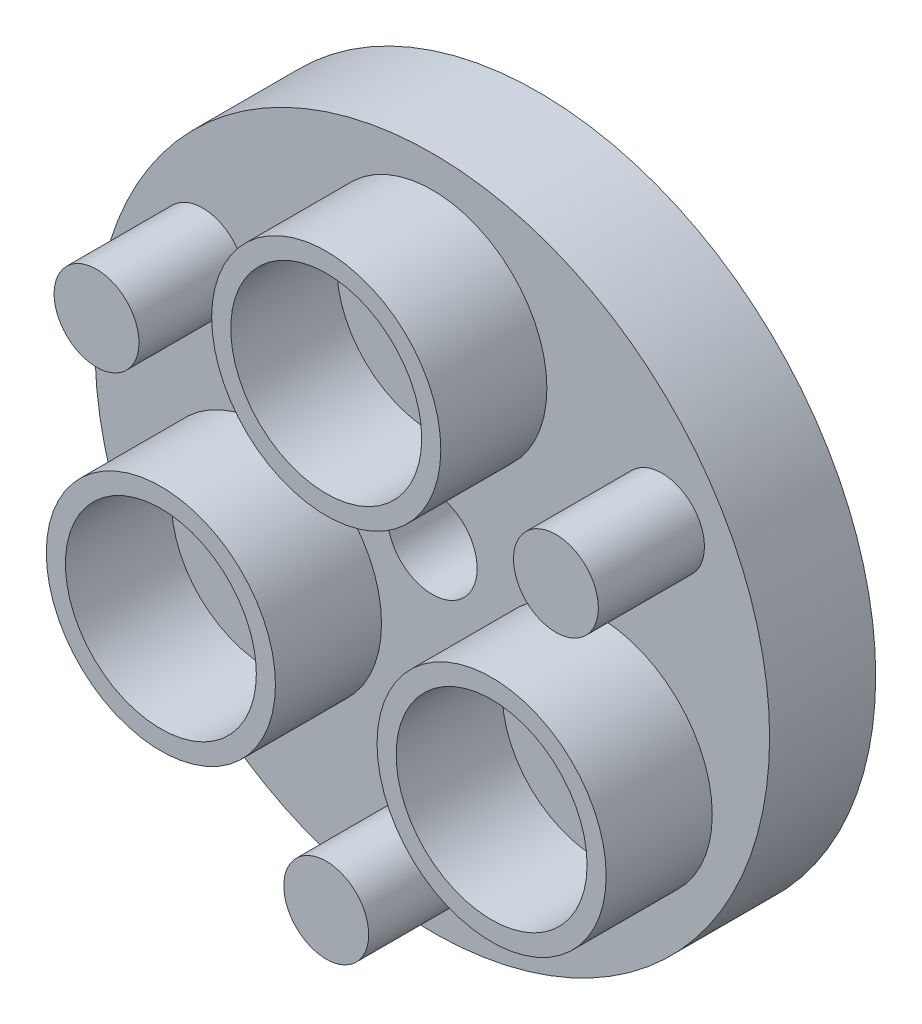
SolidWorks part; units mm, degrees
ref_plane "Plan de face" through (0, 0, 0) normal (0, 0, 1) x (1, 0, 0)
ref_plane "Plan de dessus" through (0, 0, 0) normal (0, 1, 0) x (1, 0, 0)
ref_plane "Plan de droite" through (0, 0, 0) normal (1, 0, 0) x (0, 0, -1)
sketch "Esquisse1" plane through (0, 0, 0) normal (0, 0, 1) x (1, 0, 0)
  circle A2 centre (0, 0) radius 31.7949
  circle A8 centre (0, -25.641) radius 4.1026
  circle A9 centre (-22.2058, 12.8205) radius 4.1026
  circle A10 centre (22.2058, 12.8205) radius 4.1026
  circle A11 centre (15.9882, -9.2308) radius 11
  circle A12 centre (-15.9882, -9.2308) radius 11
  circle A13 centre (0, 18.4615) radius 11
  dimension "D1" = 22
sketch "Esquisse4" plane through (0, 0, 0) normal (0, 0, 1) x (1, 0, 0)
  circle A0 centre (0, 0) radius 31.7949 construction
  circle A1 centre (0, 0) radius 31.7949
  point P7 (22.2058, 12.8205)
extrude "Boss.-Extru.1" add sketch "Esquisse4" against normal blind 10
sketch "Esquisse5" plane through (0, 0, 0) normal (0, 0, 1) x (1, 0, 0)
  line L0 (0, 0) -> (0, 18) construction
  line L1 (0, 0) -> (15.5885, -9) construction
  line L2 (0, 0) -> (-15.5885, -9) construction
  line L3 (0, 0) -> (0, -21) construction
  line L4 (0, 0) -> (-18.1865, 10.5) construction
  line L5 (0, 0) -> (18.1865, 10.5) construction
  circle A0 centre (15.5885, -9) radius 10.8
  circle A1 centre (-15.5885, -9) radius 10.8
  circle A2 centre (0, 18) radius 10.8
  circle A3 centre (0, 18) radius 9
  circle A4 centre (-15.5885, -9) radius 9
  circle A5 centre (15.5885, -9) radius 9
  circle A6 centre (21.6506, 12.5) radius 4
  circle A7 centre (-21.6506, 12.5) radius 4
  circle A8 centre (0, -25) radius 4
  point P21 (0, 0)
  point P22 (0, 0)
  dimension "D1" = 18
  dimension "D4" = 21.6
  dimension "D5" = 18
  dimension "D6" = 8
  dimension "D2" = 18
  dimension "D3" = 18
  dimension "D7" = 25
extrude "Boss.-Extru.2" add sketch "Esquisse5" along normal blind 10
sketch "Esquisse6" plane through (0, 0, -10) normal (0, 0, -1) x (-1, 0, 0)
  line L0 (0, 0) -> (0, 43.4925) construction
  circle A6 centre (0, 25.641) radius 4
  circle A7 centre (0, 0) radius 31.7949 construction
  circle A8 centre (22.2058, 12.8205) radius 4
  circle A9 centre (22.2058, -12.8205) radius 4
  circle A10 centre (0, -25.641) radius 4
  circle A11 centre (-22.2058, -12.8205) radius 4
  circle A12 centre (-22.2058, 12.8205) radius 4
  point P16 (0, 0)
  point P20 (0, 0)
  dimension "D2" = 25.641
  dimension "D3" = 8
  dimension "D1" = 6
extrude "Enlèv. mat.-Extru.2" cut sketch "Esquisse6" against normal blind 5
sketch "Esquisse8" plane through (0, 0, -10) normal (0, 0, -1) x (-1, 0, 0)
  circle A0 centre (0, 0) radius 4.2225
extrude "Enlèv. mat.-Extru.4" cut sketch "Esquisse8" against normal up to surface (10 mm away) up to face at (4, -25, 0)
